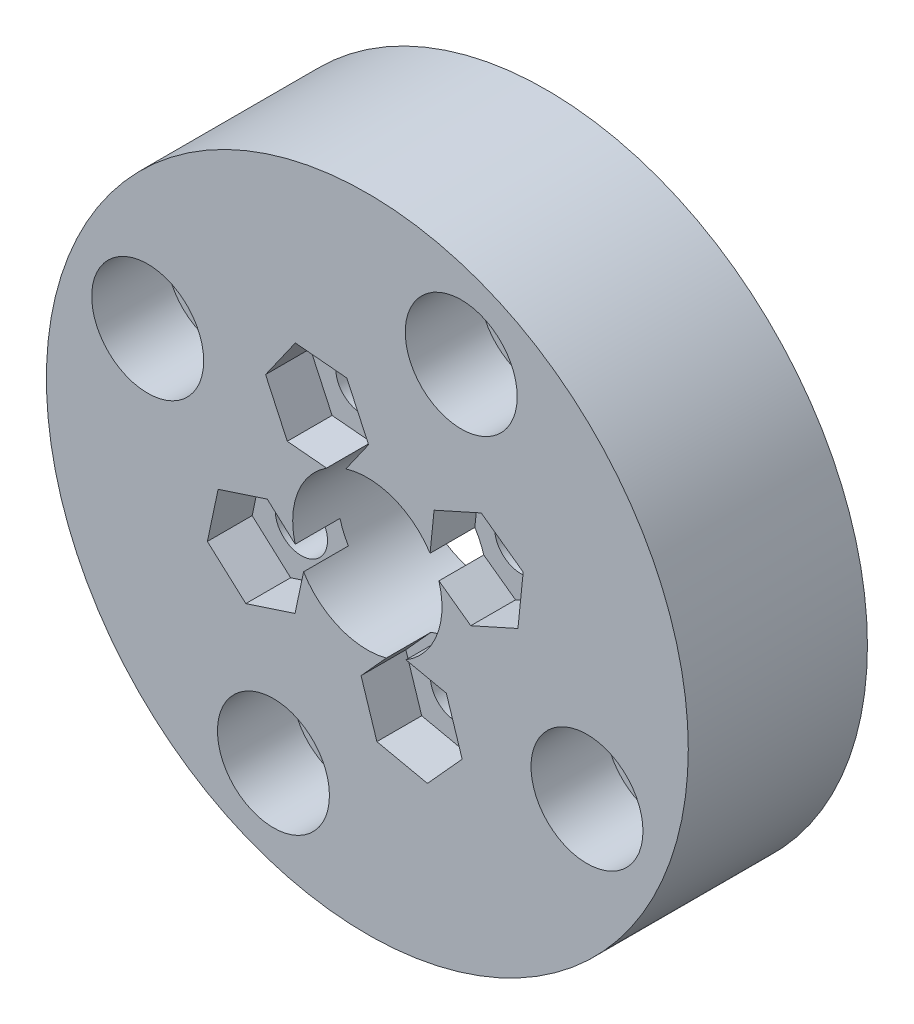
SolidWorks part; units mm, degrees
ref_plane "Plan de face" through (0, 0, 0) normal (0, 0, 1) x (1, 0, 0)
ref_plane "Plan de dessus" through (0, 0, 0) normal (0, 1, 0) x (1, 0, 0)
ref_plane "Plan de droite" through (0, 0, 0) normal (1, 0, 0) x (0, 0, -1)
sketch "Esquisse1" plane through (0, 0, 0) normal (0, 0, 1) x (1, 0, 0)
  circle A0 centre (0, 0) radius 11.25
  circle A1 centre (0, 0) radius 21.5
  dimension "D1" = 22.5
  dimension "D2" = 43
extrude "Boss.-Extru.1" add sketch "Esquisse1" along normal blind 12
sketch "Esquisse2" plane through (0, 0, 12) normal (0, 0, 1) x (1, 0, 0)
  line L0 (-14.7134, 6.2862) -> (-5.9572, 14.8496) construction
  line L1 (-5.9572, 14.8496) -> (6.2896, 14.712) construction
  line L2 (-6.2896, -14.712) -> (5.9572, -14.8496) construction
  line L3 (5.9572, -14.8496) -> (14.7134, -6.2862) construction
  line L4 (-5.9572, 14.8496) -> (0, 0) construction
  line L5 (0, 0) -> (5.9572, -14.8496) construction
  circle A0 centre (0, 0) radius 16 construction
  circle A2 centre (-14.7134, 6.2862) radius 2.5
  circle A3 centre (6.2896, 14.712) radius 2.5
  circle A4 centre (14.7134, -6.2862) radius 2.5
  circle A6 centre (-6.2896, -14.712) radius 2.5
  dimension "D1" = 32
  dimension "D3" = 5
  dimension "D2" = 22.63
extrude "Enlèv. mat.-Extru.1" cut sketch "Esquisse2" against normal through all
sketch "Esquisse4" plane through (0, 0, 12) normal (0, 0, 1) x (1, 0, 0)
  circle A0 centre (-6.2896, -14.712) radius 3.75
  circle A2 centre (14.7134, -6.2862) radius 3.75
  circle A3 centre (6.2896, 14.712) radius 3.75
  circle A5 centre (-14.7134, 6.2862) radius 3.75
  dimension "D1" = 7.5
extrude "Enlèv. mat.-Extru.2" cut sketch "Esquisse4" against normal blind 5
sketch "Esquisse5" plane through (0, 0, 12) normal (0, 0, 1) x (1, 0, 0)
  circle A0 centre (0, 0) radius 11.25
extrude "Boss.-Extru.2" add sketch "Esquisse5" against normal blind 8
sketch "Esquisse6" plane through (0, 0, 4) normal (0, 0, -1) x (-1, 0, 0)
  circle A0 centre (0, 0) radius 5
  dimension "D1" = 10
extrude "Enlèv. mat.-Extru.3" cut sketch "Esquisse6" against normal blind 50
sketch "Esquisse7" plane through (0, 0, 4) normal (0, 0, -1) x (-1, 0, 0)
  line L0 (6.2896, -14.712) -> (-6.2896, 14.712) construction
  line L1 (14.7134, 6.2862) -> (-14.7134, -6.2862) construction
  line L2 (14.7134, 6.2862) -> (6.2896, -14.712) construction
  line L3 (6.2896, -14.712) -> (-14.7134, -6.2862) construction
  line L4 (-14.7134, -6.2862) -> (-6.2896, 14.712) construction
  line L5 (-6.2896, 14.712) -> (14.7134, 6.2862) construction
  circle A0 centre (0, 0) radius 8 construction
  circle A1 centre (7.4202, -2.99) radius 1.75
  circle A2 centre (-2.9658, -7.43) radius 1.75
  circle A3 centre (-7.2795, 3.318) radius 1.75
  circle A4 centre (3.3673, 7.2568) radius 1.75
  dimension "D1" = 16
  dimension "D2" = 3.5
extrude "Enlèv. mat.-Extru.4" cut sketch "Esquisse7" against normal blind 11
sketch "Esquisse8" plane through (0, 0, 12) normal (0, 0, 1) x (1, 0, 0)
  line L0 (4.1193, 1.8991) -> (-4.1262, -1.9181) construction
  line L1 (-6.8173, 7.5683) -> (-5.3621, 4.4247)
  line L2 (-5.3621, 4.4247) -> (-1.912, 4.1132)
  line L3 (-1.912, 4.1132) -> (0.0828, 6.9453)
  line L4 (0.0828, 6.9453) -> (-1.3725, 10.0889)
  line L5 (-1.3725, 10.0889) -> (-4.8226, 10.4004)
  line L6 (-4.8226, 10.4004) -> (-6.8173, 7.5683)
  line L7 (7.6307, 6.7643) -> (4.4706, 5.3453)
  line L8 (4.4706, 5.3453) -> (4.1193, 1.8991)
  line L9 (4.1193, 1.8991) -> (6.9282, -0.1282)
  line L10 (6.9282, -0.1282) -> (10.0884, 1.2907)
  line L11 (10.0884, 1.2907) -> (10.4396, 4.737)
  line L12 (10.4396, 4.737) -> (7.6307, 6.7643)
  line L13 (6.352, -8.1603) -> (5.2914, -4.8626)
  line L14 (5.2914, -4.8626) -> (1.9051, -4.1322)
  line L15 (1.9051, -4.1322) -> (-0.4205, -6.6996)
  line L16 (-0.4205, -6.6996) -> (0.6401, -9.9973)
  line L17 (0.6401, -9.9973) -> (4.0264, -10.7277)
  line L18 (4.0264, -10.7277) -> (6.352, -8.1603)
  line L19 (-6.7015, 0.3987) -> (-9.9956, -0.6732)
  line L20 (-9.9956, -0.6732) -> (-10.7143, -4.0619)
  line L21 (-10.7143, -4.0619) -> (-8.139, -6.3787)
  line L22 (-8.139, -6.3787) -> (-4.8449, -5.3068)
  line L23 (-4.8449, -5.3068) -> (-4.1262, -1.9181)
  line L24 (-4.1262, -1.9181) -> (-6.7015, 0.3987)
  line L25 (-1.912, 4.1132) -> (1.9051, -4.1322) construction
  line L26 (-4.8226, 10.4004) -> (-1.912, 4.1132) construction
  circle A0 centre (-3.3673, 7.2568) radius 3 construction
  circle A1 centre (7.2795, 3.318) radius 3 construction
  circle A2 centre (2.9658, -7.43) radius 3 construction
  circle A3 centre (-7.4202, -2.99) radius 3 construction
  point P28 (-0.0034, -0.0095)
  dimension "D1" = 6
extrude "Enlèv. mat.-Extru.5" cut sketch "Esquisse8" against normal blind 3
